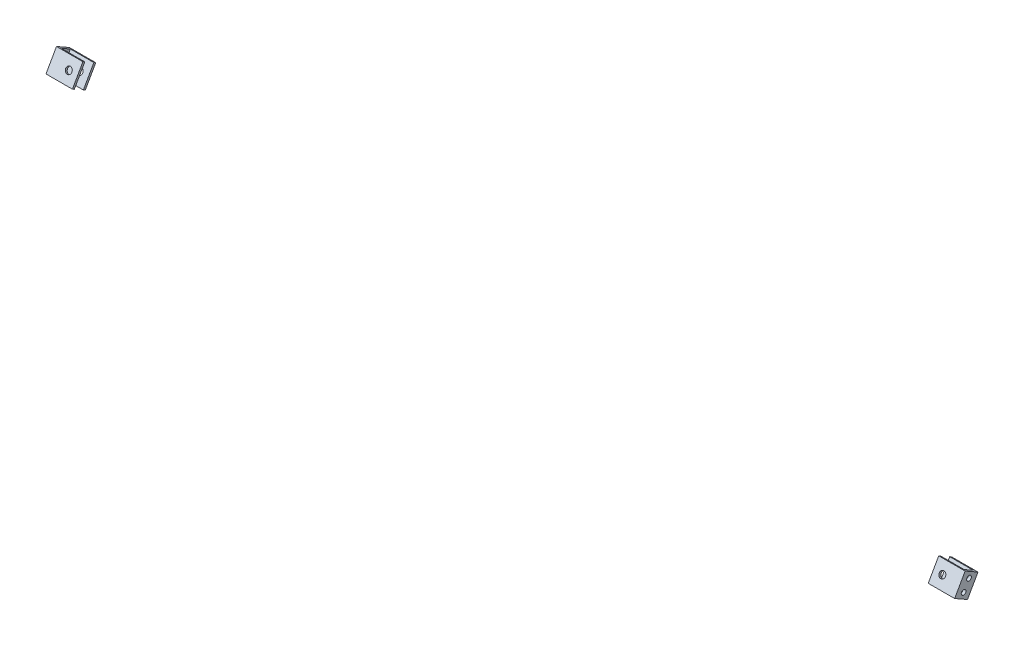
SolidWorks part; units mm, degrees
ref_plane "Front Plane" through (0, 0, 0) normal (0, 0, 1) x (1, 0, 0)
ref_plane "Top Plane" through (0, 0, 0) normal (0, 1, 0) x (1, 0, 0)
ref_plane "Right Plane" through (0, 0, 0) normal (1, 0, 0) x (0, 0, -1)
ref_plane "Plane1" through (0, -217.9452, -384.9482) normal (0, -0.4927, -0.8702) x (-1, 0, 0)
sketch "Sketch1" plane through (0, -217.9452, -384.9482) normal (0, -0.4927, -0.8702) x (-1, 0, 0)
  line L0 (487.45, 1279.1709) -> (468.654, 1279.1709) construction
  line L1 (487.45, 1279.1709) -> (468.654, 1279.1709) construction
  line L2 (487.45, 1290.6009) -> (487.45, 1267.7409)
  line L3 (487.45, 1427.6969) -> (487.45, 1247.6609) construction
  line L4 (487.45, 1290.6009) -> (459.129, 1290.6009)
  line L5 (459.129, 1290.6009) -> (459.129, 1267.7409)
  line L6 (459.129, 1267.7409) -> (487.45, 1267.7409)
  circle A0 centre (468.654, 1279.1709) radius 3.3782
  point P6 (487.45, 1279.1709)
  dimension "D1" = 6.7564
  dimension "D2" = 11.43
  dimension "D3" = 9.525
extrude "Boss-Extrude1" add sketch "Sketch1" along normal mid plane 15.875
sketch "Sketch2" plane through (0, 1103.1987, -624.5954) normal (0, -0.8702, 0.4927) x (1, 0, 0)
  line L0 (-487.45, -442.3632) -> (-459.129, -442.3632) construction
  line L1 (-484.275, -436.807) -> (-452.4806, -436.807)
  line L2 (-484.275, -436.807) -> (-484.275, -447.9195)
  line L3 (-484.275, -447.9195) -> (-452.4806, -447.9195)
  line L4 (-452.4806, -436.807) -> (-452.4806, -447.9195)
  line L8 (-459.129, -434.4257) -> (-487.45, -434.4257)
  line L9 (-487.45, -434.4257) -> (-487.45, -450.3007)
  line L10 (-487.45, -450.3007) -> (-459.129, -450.3007)
  line L11 (-459.129, -450.3007) -> (-459.129, -434.4257)
  line L12 (-459.129, -434.4257) -> (-487.45, -434.4257) construction
  line L13 (-487.45, -434.4257) -> (-487.45, -450.3007) construction
  line L14 (-487.45, -450.3007) -> (-459.129, -450.3007) construction
  line L15 (-459.129, -450.3007) -> (-459.129, -434.4257) construction
  dimension "D1" = 11.1125
  dimension "D3" = 3.175
  dimension "D2" = 0
extrude "Cut-Extrude1" cut sketch "Sketch2" against normal through all
sketch "Sketch3" plane through (-487.45, 0, 0) normal (-1, 0, 0) x (0, 0, 1)
  line L0 (-1020.8064, 905.1465) -> (-1009.5436, 885.2535) construction
  line L1 (-1022.0823, 891.2893) -> (-1008.2677, 899.1107) construction
  line L4 (-1002.6363, 889.1642) -> (-1013.8991, 909.0572)
  line L5 (-1013.8991, 909.0572) -> (-1027.7137, 901.2358)
  line L6 (-1027.7137, 901.2358) -> (-1016.4509, 881.3428)
  line L7 (-1016.4509, 881.3428) -> (-1002.6363, 889.1642)
  line L8 (-1002.6363, 889.1642) -> (-1013.8991, 909.0572) construction
  line L9 (-1013.8991, 909.0572) -> (-1027.7137, 901.2358) construction
  line L10 (-1027.7137, 901.2358) -> (-1016.4509, 881.3428) construction
  line L11 (-1016.4509, 881.3428) -> (-1002.6363, 889.1642) construction
  circle A0 centre (-1018.0658, 900.3059) radius 2.5527
  circle A1 centre (-1012.2842, 890.0941) radius 2.5527
  circle A2 centre (0, 890.8219) radius 2.5527
  dimension "D2" = 5.1054
  dimension "D3" = 5.1054
  dimension "D4" = 5.8674
  dimension "D5" = 5.8674
  dimension "D1" = 0
extrude "Cut-Extrude2" cut sketch "Sketch3" against normal through all
mirror "Mirror2" about plane through (0, 0, 0) normal (1, 0, 0) of bodies 103
